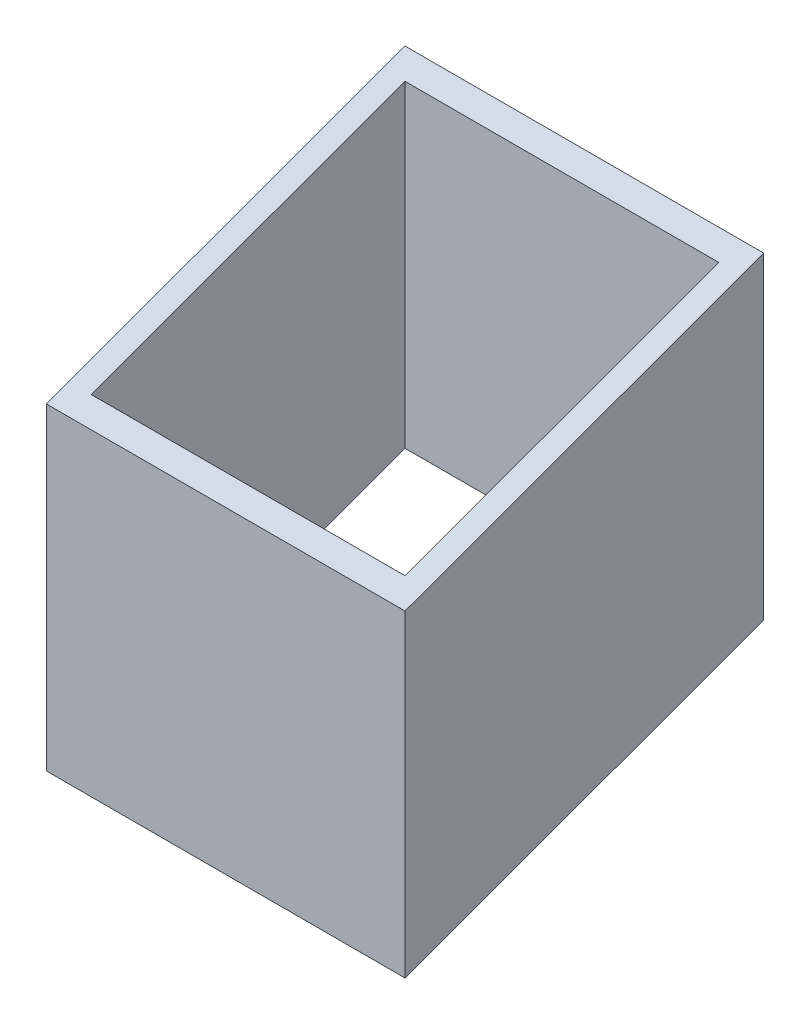
SolidWorks part; units mm, degrees
ref_plane "Front Plane" through (0, 0, 0) normal (0, 0, 1) x (1, 0, 0)
ref_plane "Top Plane" through (0, 0, 0) normal (0, 1, 0) x (1, 0, 0)
ref_plane "Right Plane" through (0, 0, 0) normal (1, 0, 0) x (0, 0, -1)
sketch "Sketch1" plane through (0, 0, 0) normal (0, 1, 0) x (1, 0, 0)
  line L1 (0, 0) -> (40, 0)
  line L2 (0, 0) -> (0, 40)
  line L3 (0, 40) -> (40, 40)
  line L4 (40, 0) -> (40, 40)
  dimension "D1" = 40
  dimension "D2" = 40
extrude "Boss-Extrude1" add sketch "Sketch1" along normal blind 50
sketch "Sketch2" plane through (0, 0, 0) normal (0, -1, 0) x (1, 0, 0)
  line L0 (2.5, 0) -> (2.5, -2.5) construction
  line L1 (0, 0) -> (40, 0) construction
  line L2 (2.5, -2.5) -> (0, -2.5) construction
  line L3 (0, -40) -> (0, 0) construction
  line L4 (2.5, -40) -> (2.5, -37.5) construction
  line L5 (40, -40) -> (0, -40) construction
  line L6 (2.5, -37.5) -> (0, -37.5) construction
  line L7 (37.5, -40) -> (37.5, -37.5) construction
  line L8 (37.5, -37.5) -> (40, -37.5) construction
  line L9 (40, 0) -> (40, -40) construction
  line L10 (37.5, 0) -> (37.5, -2.5) construction
  line L11 (37.5, -2.5) -> (40, -2.5) construction
  line L12 (2.5, -2.5) -> (2.5, -37.5)
  line L13 (2.5, -37.5) -> (37.5, -37.5)
  line L14 (37.5, -37.5) -> (37.5, -2.5)
  line L15 (37.5, -2.5) -> (2.5, -2.5)
  dimension "D1" = 2.5
  dimension "D2" = 2.5
  dimension "D3" = 2.5
  dimension "D4" = 2.5
  dimension "D5" = 2.5
  dimension "D6" = 2.5
  dimension "D7" = 2.5
  dimension "D8" = 2.5
extrude "Cut-Extrude1" cut sketch "Sketch2" against normal through all
sketch "Sketch3" plane through (0, 0, 0) normal (-1, 0, 0) x (0, 0, 1)
  line L0 (0, 0) -> (-40, 14.5588)
  line L1 (-40, 50) -> (-40, 0) construction
  line L2 (0, 35.4412) -> (-40, 50)
  line L3 (0, 50) -> (0, 0) construction
  line L4 (-40, 0) -> (0, 0) construction
  line L5 (0, 35.4412) -> (0, 0)
  line L6 (-40, 50) -> (0, 50)
  line L7 (0, 50) -> (0, 35.4412)
  line L8 (0, 0) -> (-40, 0)
  line L9 (-40, 0) -> (-40, 14.5588)
  line M3 (-40, 0) -> (0, 0)
  line M4 (0, 0) -> (0, 50)
  line M5 (0, 50) -> (-40, 50)
  line M6 (-40, 50) -> (-40, 0)
  dimension "D1" = 20
  dimension "D2" = 70
  dimension "D3" = 35.4412
extrude "Cut-Extrude2" cut sketch "Sketch3" against normal through all contours L0 M3 M6 | L2 M4 M5
